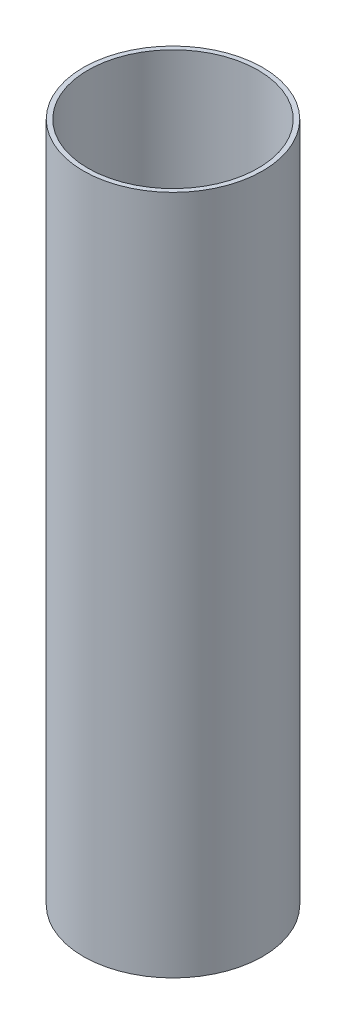
SolidWorks part; units mm, degrees
material "Corrugated Paper"
ref_plane "Front Plane" through (0, 0, 0) normal (0, 0, 1) x (1, 0, 0)
ref_plane "Top Plane" through (0, 0, 0) normal (0, 1, 0) x (1, 0, 0)
ref_plane "Right Plane" through (0, 0, 0) normal (1, 0, 0) x (0, 0, -1)
sketch "Sketch1" plane through (0, 0, 0) normal (0, 1, 0) x (1, 0, 0)
  circle A0 centre (0, 0) radius 40.1574
  circle A1 centre (0, 0) radius 38.1
  dimension "D1" = 76.2
  dimension "D2" = 80.3148
extrude "Boss-Extrude1" add sketch "Sketch1" against normal blind 304.8
